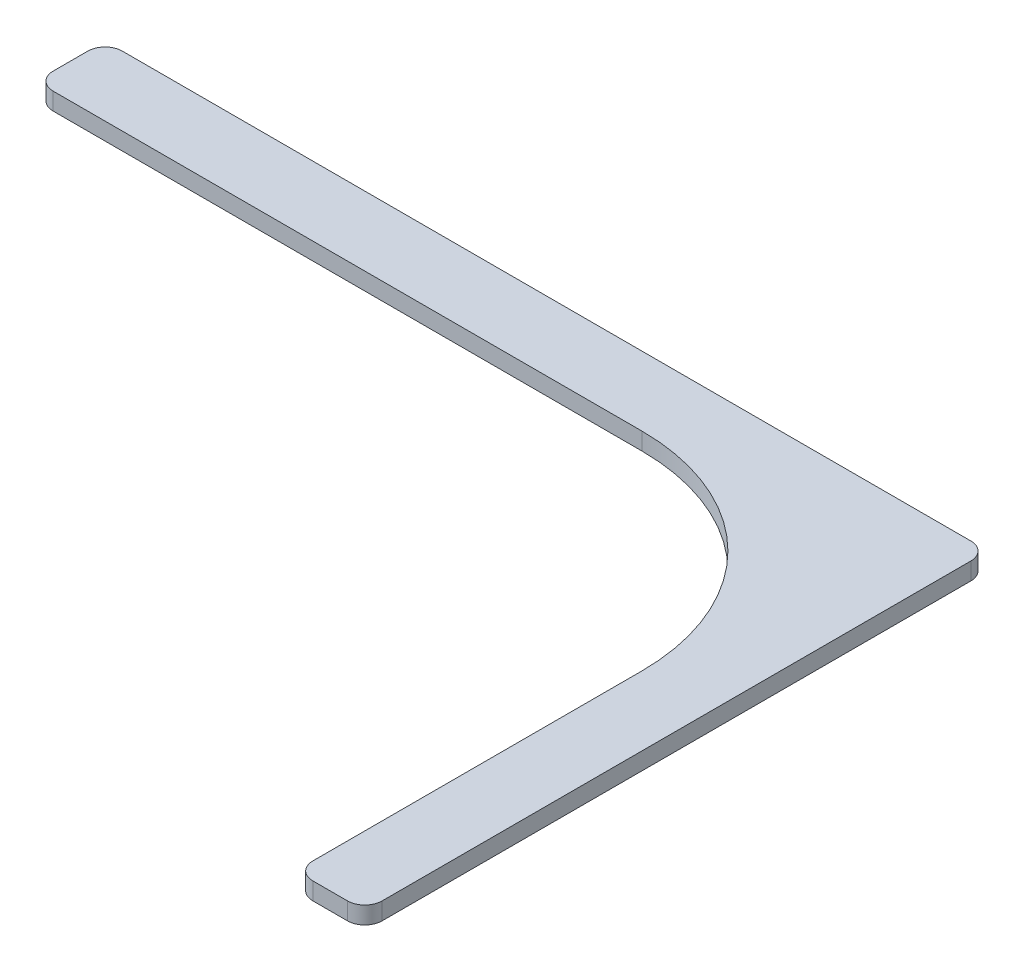
SolidWorks part; units mm, degrees
ref_plane "Front Plane" through (0, 0, 0) normal (0, 0, 1) x (1, 0, 0)
ref_plane "Top Plane" through (0, 0, 0) normal (0, 1, 0) x (1, 0, 0)
ref_plane "Right Plane" through (0, 0, 0) normal (1, 0, 0) x (0, 0, -1)
sketch "Sketch1" plane through (0, 0, 0) normal (0, 1, 0) x (1, 0, 0)
  line L0 (0, 0) -> (0, 228.6)
  line L1 (0, 228.6) -> (-323.85, 228.6)
  line L2 (-323.85, 228.6) -> (-323.85, 203.2)
  line L3 (-323.85, 203.2) -> (-25.4, 203.2)
  line L4 (-25.4, 0) -> (0, 0)
  line L6 (-25.4, 0) -> (-25.4, 203.2)
  dimension "D1" = 228.6
  dimension "D2" = 323.85
  dimension "D3" = 25.4
  dimension "D4" = 25.4
extrude "Boss-Extrude1" add sketch "Sketch1" along normal blind 6.35
fillet "Fillet1" radius 6.35 5 edges at (-323.85, 3.175, -228.6) (-323.85, 3.175, -203.2) (0, 3.175, 0) (0, 3.175, -228.6) (-25.4, 3.175, 0)
fillet "Fillet2" radius 76.2 1 edges at (-25.4, 3.175, -203.2)
